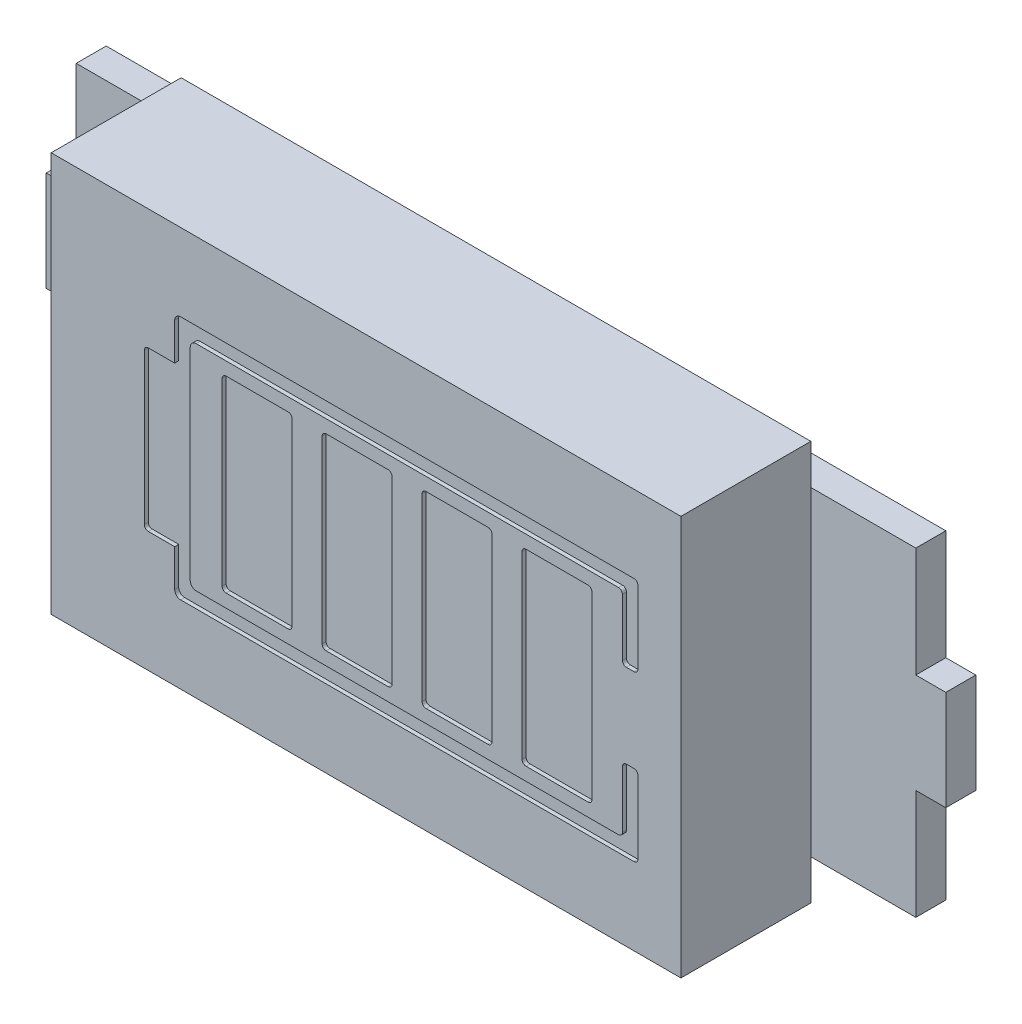
SolidWorks part; units mm, degrees
ref_plane "Front Plane" through (0, 0, 0) normal (0, 0, 1) x (1, 0, 0)
ref_plane "Top Plane" through (0, 0, 0) normal (0, 1, 0) x (1, 0, 0)
ref_plane "Right Plane" through (0, 0, 0) normal (1, 0, 0) x (0, 0, -1)
sketch "Sketch8" plane through (0, 0, 0) normal (0, 0, 1) x (1, 0, 0)
  line L0 (-22.5, -2.5) -> (-21, -2.5)
  line L1 (-21, -2.5) -> (-21, -8)
  line L2 (-21, -8) -> (21, -8)
  line L3 (21, -8) -> (21, -2.5)
  line L4 (21, -2.5) -> (22.5, -2.5)
  line L5 (22.5, -2.5) -> (22.5, 2.5)
  line L6 (22.5, 2.5) -> (21, 2.5)
  line L7 (21, 2.5) -> (21, 8)
  line L8 (21, 8) -> (-21, 8)
  line L9 (-21, 8) -> (-21, 2.5)
  line L10 (-21, 2.5) -> (-22.5, 2.5)
  line L11 (-22.5, 2.5) -> (-22.5, -2.5)
extrude "Boss-Extrude2" add sketch "Sketch8" against normal blind 1.5 separate body
ref_plane "Plane5" through (0, 0, 6.5) normal (0, 0, 1) x (1, 0, 0)
sketch "Sketch12" plane through (0, 0, 6.5) normal (0, 0, 1) x (1, 0, 0)
  line L0 (-15.75, -10) -> (15.75, -10)
  line L1 (15.75, -10) -> (15.75, 10)
  line L2 (15.75, 10) -> (-15.75, 10)
  line L3 (-15.75, 10) -> (-15.75, -10)
  line L4 (0, 10) -> (0, -17.8364) construction
  line L5 (-21, -2.5) -> (-21, -8) construction
  line L8 (21, -8) -> (21, -2.5) construction
  point P11 (-43.0151, -9.8415)
  dimension "D1" = 31.5
  dimension "D2" = 5.25
  dimension "D3" = 5.25
  dimension "D4" = 90
  dimension "D5" = 90
extrude "Boss-Extrude3" add sketch "Sketch12" against normal blind 6.5 separate body
sketch "Sketch13" plane through (0, 0, 6.5) normal (0, 0, 1) x (1, 0, 0)
  line L0 (12.8238, -5.3552) -> (-8.7957, -5.3552)
  line L1 (-8.7957, -5.3552) -> (-8.7957, 5.3552)
  line L2 (-8.7957, 5.3552) -> (12.8238, 5.3552)
  line L3 (12.8238, 5.3552) -> (12.8238, 2.0974)
  line L4 (12.8238, 2.0974) -> (13.6003, 2.0974)
  line L5 (13.6003, 2.0974) -> (13.6003, 6.1318)
  line L6 (13.6003, 6.1318) -> (-9.5722, 6.1318)
  line L7 (-9.5722, 6.1318) -> (-9.5722, 3.9761)
  line L8 (-9.5722, 3.9761) -> (-11.0938, 3.9761)
  line L9 (-11.0938, 3.9761) -> (-11.0938, -3.9761)
  line L10 (-11.0938, -3.9761) -> (-9.5722, -3.9761)
  line L11 (-9.5722, -3.9761) -> (-9.5722, -6.1318)
  line L12 (-9.5722, -6.1318) -> (13.6003, -6.1318)
  line L13 (13.6003, -6.1318) -> (13.6003, -2.0974)
  line L14 (13.6003, -2.0974) -> (12.8238, -2.0974)
  line L15 (12.8238, -2.0974) -> (12.8238, -5.3552)
extrude "Cut-Extrude6" cut sketch "Sketch13" against normal blind 0.2
sketch "Sketch18" plane through (0, 0, 6.5) normal (0, 0, 1) x (1, 0, 0)
  line L0 (-2.2, -4.7) -> (1.3, -4.7)
  line L1 (1.3, -4.7) -> (1.3, 4.7)
  line L2 (1.3, 4.7) -> (-2.2, 4.7)
  line L3 (-2.2, 4.7) -> (-2.2, -4.7)
extrude "Cut-Extrude7" cut sketch "Sketch18" against normal blind 0.2
sketch "Sketch19" plane through (0, 0, 6.5) normal (0, 0, 1) x (1, 0, 0)
  line L0 (-7.2, -4.7) -> (-3.7, -4.7)
  line L1 (-3.7, -4.7) -> (-3.7, 4.7)
  line L2 (-3.7, 4.7) -> (-7.2, 4.7)
  line L3 (-7.2, 4.7) -> (-7.2, -4.7)
extrude "Cut-Extrude8" cut sketch "Sketch19" against normal blind 0.2
sketch "Sketch24" plane through (0, 0, 6.5) normal (0, 0, 1) x (1, 0, 0)
  line L0 (2.8, -4.7) -> (6.3, -4.7)
  line L1 (6.3, -4.7) -> (6.3, 4.7)
  line L2 (6.3, 4.7) -> (2.8, 4.7)
  line L3 (2.8, 4.7) -> (2.8, -4.7)
extrude "Cut-Extrude9" cut sketch "Sketch24" against normal blind 0.2
sketch "Sketch25" plane through (0, 0, 6.5) normal (0, 0, 1) x (1, 0, 0)
  line L0 (7.8, -4.7) -> (11.3, -4.7)
  line L1 (11.3, -4.7) -> (11.3, 4.7)
  line L2 (11.3, 4.7) -> (7.8, 4.7)
  line L3 (7.8, 4.7) -> (7.8, -4.7)
extrude "Cut-Extrude10" cut sketch "Sketch25" against normal blind 0.2
fillet "Fillet3" radius 0.2 26 edges at (13.6003, -6.1318, 6.4) (-11.0938, -3.9761, 6.4) (-7.2, 4.7, 6.4) (7.8, 4.7, 6.4) (2.8, 4.7, 6.4) (12.8238, 5.3552, 6.4) (-11.0938, 3.9761, 6.4) (13.6003, 6.1318, 6.4) (-2.2, 4.7, 6.4) (12.8238, -5.3552, 6.4) (7.8, -4.7, 6.4) (12.8238, 2.0974, 6.4) (-2.2, -4.7, 6.4) (-3.7, -4.7, 6.4) (11.3, 4.7, 6.4) (12.8238, -2.0974, 6.4) (2.8, -4.7, 6.4) (13.6003, -2.0974, 6.4) (13.6003, 2.0974, 6.4) (-7.2, -4.7, 6.4) (1.3, 4.7, 6.4) (1.3, -4.7, 6.4) (11.3, -4.7, 6.4) (6.3, 4.7, 6.4) (-3.7, 4.7, 6.4) (6.3, -4.7, 6.4)
fillet "Fillet4" radius 0.3 4 edges at (-9.5722, 6.1318, 6.4) (-9.5722, -6.1318, 6.4) (-8.7957, 5.3552, 6.4) (-8.7957, -5.3552, 6.4)
